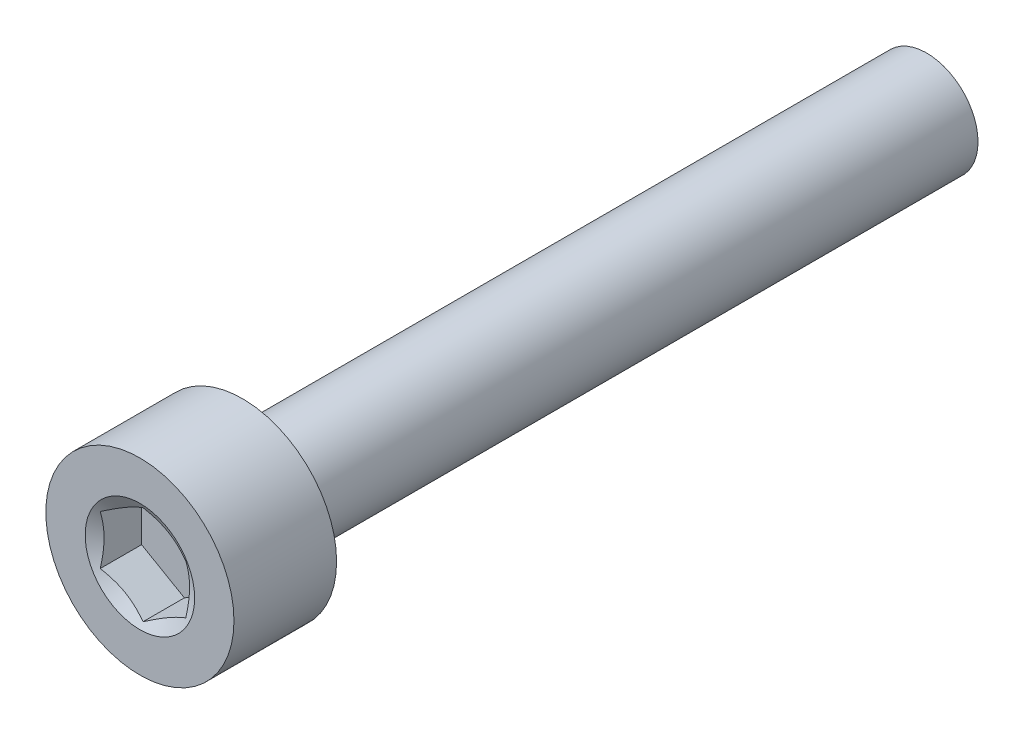
SolidWorks part; units mm, degrees
ref_plane "Плоскость1" through (0, 0, 0) normal (0, 0, 1) x (1, 0, 0)
ref_plane "Плоскость2" through (0, 0, 0) normal (0, 1, 0) x (1, 0, 0)
ref_plane "Плоскость3" through (0, 0, 0) normal (1, 0, 0) x (0, 0, -1)
sketch "Ske1" plane through (0, 0, 0) normal (0, 0, 1) x (1, 0, 0)
  circle A0 centre (0, 0) radius 2.75
  dimension "Head_Dia" = 5.5
extrude "Base1" add sketch "Ske1" along normal blind 3
sketch "BodySke" plane through (0, 0, 0) normal (1, 0, 0) x (0, 0, -1)
  line L0 (-1.3858, 0) -> (20, 0) construction
  line L1 (0, -2.75) -> (0, 2.75) construction
  line L3 (-3, 0) -> (0, 0) construction
  line L4 (20, 1.5) -> (-3, 1.5)
  line L7 (-3, 2.75) -> (-3, -2.75) construction
  line L8 (-3, 1.5) -> (-3, 0)
  line L9 (-3, 0) -> (20, 0)
  line L10 (20, 0) -> (20, 1.5)
  line L11 (-3, 0) -> (9.169, 0) construction
  line L12 (0.5, 0) -> (0.5, 5.6548) construction
  line L13 (2, 0) -> (2, 5.6548) construction
  dimension "Diameter" = 3
  dimension "Advance" = 0.5
  dimension "Thread_nom" = 18
  dimension "Length" = 20
revolve "BaseBody" add sketch "BodySke" angle 360 about L0
cosmetic thread "ThreadCosmetic"
sketch "Ske8" plane through (0, 0, 3) normal (0, 0, 1) x (1, 0, 0)
  line L1 (0, 1.4434) -> (-1.25, 0.7217)
  line L2 (-1.25, 0.7217) -> (-1.25, -0.7217)
  line L3 (-1.25, -0.7217) -> (0, -1.4434)
  line L4 (0, -1.4434) -> (1.25, -0.7217)
  line L5 (1.25, -0.7217) -> (1.25, 0.7217)
  line L6 (1.25, 0.7217) -> (0, 1.4434)
  circle A0 centre (0, 0) radius 1.25 construction
  dimension "Width_Flats" = 2.5
extrude "Hex" cut sketch "Ske8" against normal blind 1.3
sketch "Ske9" plane through (0, 0, 3) normal (0, 0, 1) x (1, 0, 0)
  circle A1 centre (0, 0) radius 1.6
  dimension "Head_Fillet" = 3.2
extrude "Chamfer" cut sketch "Ske9" against normal through all draft 60
equation "\"Thread_length@ThreadCosmetic\" = ((sgn( (\"Length@BodySke\" - \"Advance@BodySke\" * 2.0 ) - \"Thread_nom@BodySke\" )-1)*( (\"Length@BodySke\" - \"Advance@BodySke\"  * 2.0) - \"Thread_nom@BodySke\" ))/-2+ \"Thread_nom@BodySke\""
